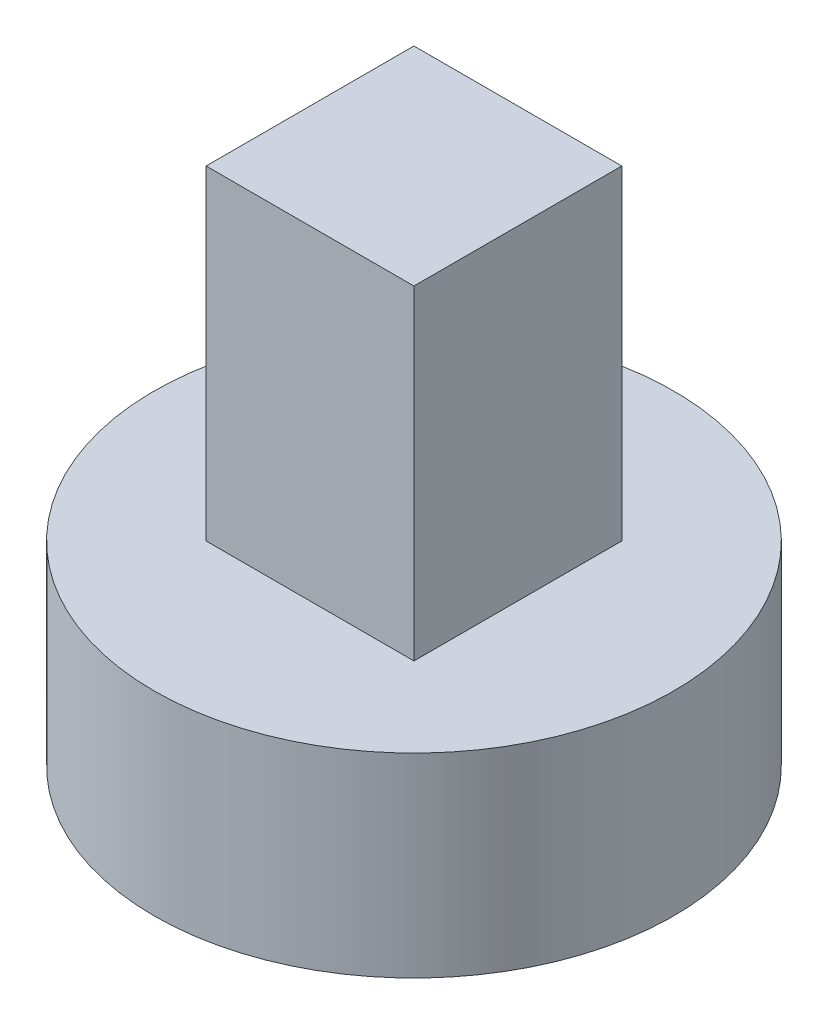
SolidWorks part; units mm, degrees
ref_plane "Спереди" through (0, 0, 0) normal (0, 0, 1) x (1, 0, 0)
ref_plane "Сверху" through (0, 0, 0) normal (0, 1, 0) x (1, 0, 0)
ref_plane "Справа" through (0, 0, 0) normal (1, 0, 0) x (0, 0, -1)
sketch "Эскиз1" plane through (0, 0, 0) normal (0, 1, 0) x (1, 0, 0)
  circle A0 centre (0, 0) radius 4
extrude "Бобышка-Вытянуть1" add sketch "Эскиз1" along normal blind 3
ref_plane "Плоскость1" through (0, 3, 0) normal (0, 1, 0) x (1, 0, 0)
sketch "Эскиз2" plane through (0, 3, 0) normal (0, 1, 0) x (1, 0, 0)
  line L0 (-1.6, 1.6) -> (1.6, 1.6)
  line L2 (-1.6, 1.6) -> (-1.6, -1.6)
  line L3 (-1.6, -1.6) -> (1.6, -1.6)
  line L4 (1.6, -1.6) -> (1.6, 1.6)
extrude "Бобышка-Вытянуть3" add sketch "Эскиз2" along normal blind 5
